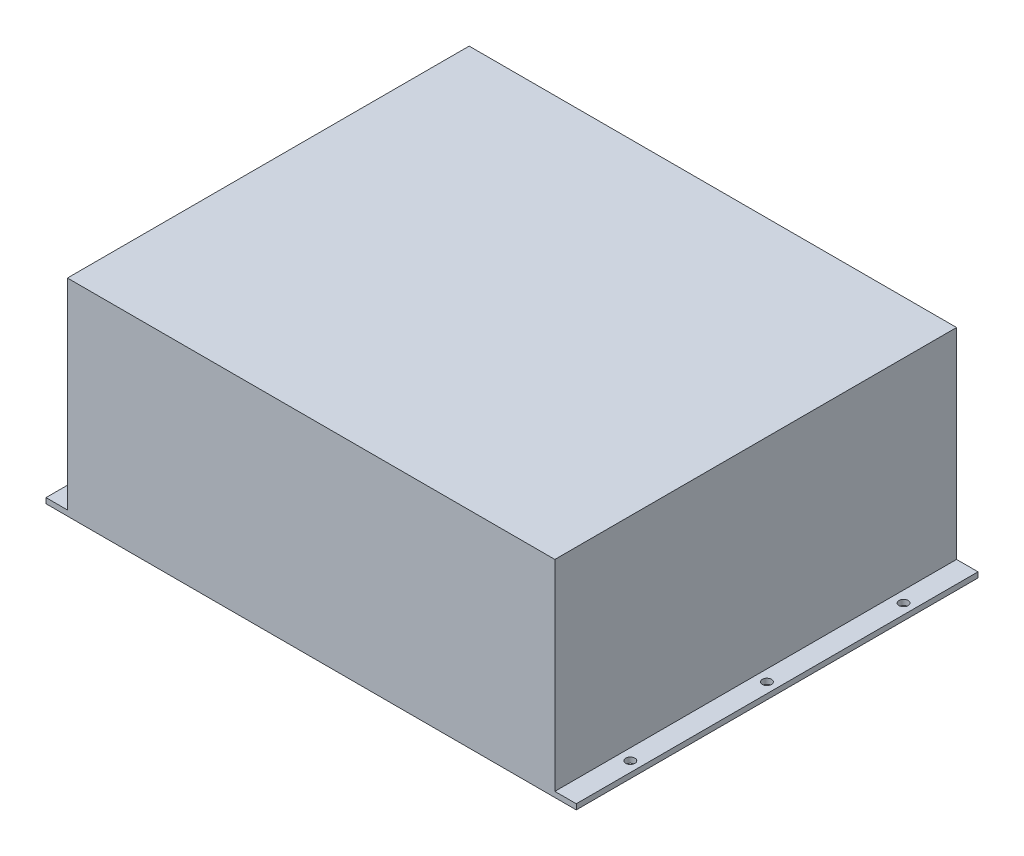
SolidWorks part; units mm, degrees
material "CA"
ref_plane "前视基准面" through (0, 0, 0) normal (0, 0, 1) x (1, 0, 0)
ref_plane "上视基准面" through (0, 0, 0) normal (0, 1, 0) x (1, 0, 0)
ref_plane "右视基准面" through (0, 0, 0) normal (1, 0, 0) x (0, 0, -1)
sketch "草图1" plane through (0, 0, 0) normal (0, 1, 0) x (1, 0, 0)
  line L1 (-91, -75) -> (91, -75)
  line L2 (-91, -75) -> (-91, 75)
  line L3 (-91, 75) -> (91, 75)
  line L4 (91, -75) -> (91, 75)
  line L5 (-91, -75) -> (91, 75) construction
  line L6 (-91, 75) -> (91, -75) construction
  point P0 (0, 0)
  dimension "D1" = 150
  dimension "D2" = 182
extrude "凸台-拉伸1" add sketch "草图1" along normal blind 77
sketch "草图2" plane through (0, 0, 0) normal (0, -1, 0) x (1, 0, 0)
  line L0 (91, -75) -> (-91, -75) construction
  line L1 (-91, 75) -> (-99, 75)
  line L2 (-91, 75) -> (-91, -75)
  line L3 (-91, -75) -> (-99, -75)
  line L4 (-99, 75) -> (-99, -75)
  dimension "D1" = 8
extrude "凸台-拉伸2" add sketch "草图2" against normal blind 2
sketch "草图3" plane through (0, 2, 0) normal (0, 1, 0) x (1, 0, 0)
  line L0 (-99, -75) -> (-99, 75) construction
  line L1 (-99, 75) -> (-91, 75) construction
  line L2 (0, 0) -> (-180.1846, 0) construction
  circle A0 centre (-95.2, 51) radius 1.7
  circle A1 centre (-95.2, -51) radius 1.7
  circle A2 centre (-95.2, 0) radius 1.7
  point P13 (0, 0)
  dimension "D1" = 3.4
  dimension "D2" = 3.8
  dimension "D3" = 24
  dimension "D4" = 3.4
extrude "切除-拉伸1" cut sketch "草图3" against normal through all
mirror "镜向1" about plane through (0, 0, 0) normal (1, 0, 0) of "切除-拉伸1", "凸台-拉伸2"
sketch "草图4" plane through (-91, 0, 0) normal (-1, 0, 0) x (0, 0, 1)
  line L0 (75, 39.5) -> (-113.5895, 39.5) construction
  line L1 (75, 77) -> (75, 2) construction
  line L2 (0, 0) -> (0, 95.4112) construction
  line L3 (75, 0) -> (-75, 0) construction
  circle A0 centre (0, 39.5) radius 4
  circle A1 centre (10, 39.5) radius 4
  circle A2 centre (-10, 39.5) radius 4
  dimension "D1" = 8
  dimension "D2" = 8
  dimension "D3" = 20
extrude "凸台-拉伸3" add sketch "草图4" along normal blind 10
